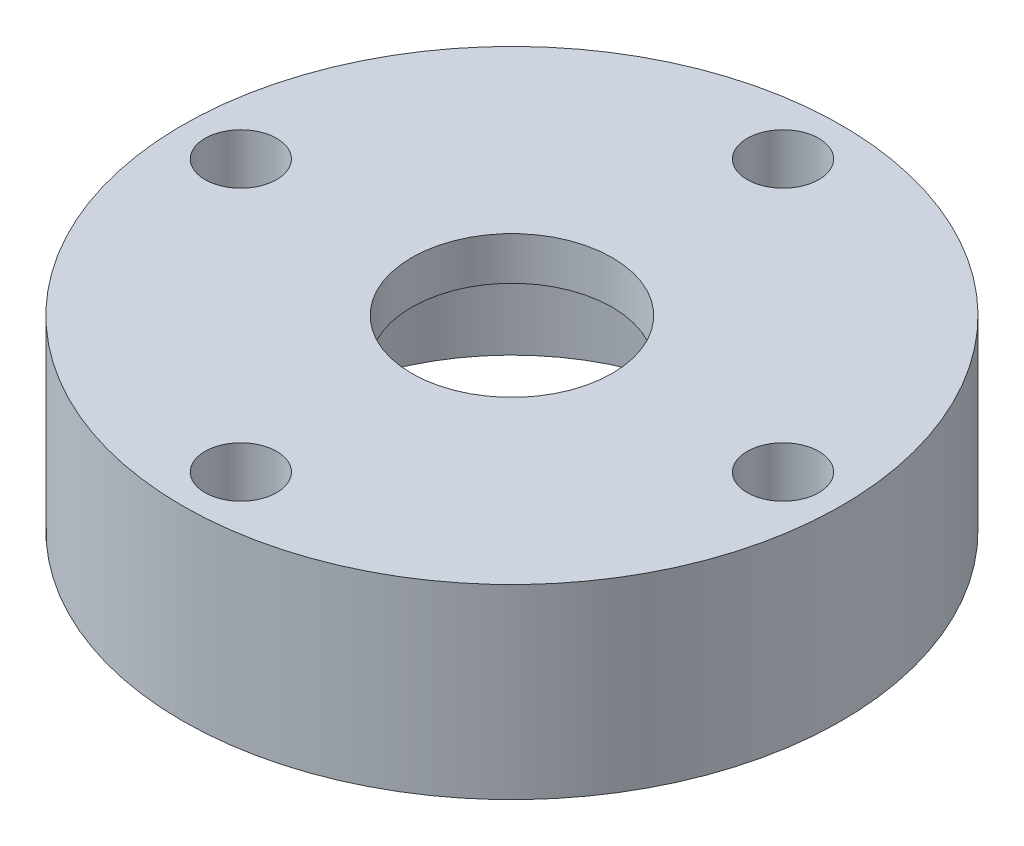
SolidWorks part; units mm, degrees
ref_plane "Спереди" through (0, 0, 0) normal (0, 0, 1) x (1, 0, 0)
ref_plane "Сверху" through (0, 0, 0) normal (0, 1, 0) x (1, 0, 0)
ref_plane "Справа" through (0, 0, 0) normal (1, 0, 0) x (0, 0, -1)
sketch "Эскиз1" plane through (0, 0, 0) normal (0, 1, 0) x (1, 0, 0)
  circle A0 centre (0, 0) radius 11.5
  circle A1 centre (0, 0) radius 7.5
extrude "Вытянуть1" add sketch "Эскиз1" along normal blind 5
sketch "Эскиз2" plane through (0, 5, 0) normal (0, 1, 0) x (1, 0, 0)
  circle A0 centre (0, 0) radius 11.5
extrude "Вытянуть3" add sketch "Эскиз2" along normal blind 1.5
sketch "Эскиз3" plane through (0, 6.5, 0) normal (0, 1, 0) x (-1, 0, 0)
  circle A0 centre (0, -9.4597) radius 1.25
  circle A1 centre (-9.4597, 0) radius 1.25
  circle A2 centre (0, 9.4597) radius 1.25
  circle A3 centre (9.4597, 0) radius 1.25
extrude "Вытянуть4" cut sketch "Эскиз3" against normal through all
sketch "Эскиз4" plane through (0, 6.5, 0) normal (0, 1, 0) x (-1, 0, 0)
  circle A0 centre (0, 0) radius 3.5
extrude "Вытянуть5" cut sketch "Эскиз4" against normal through all
